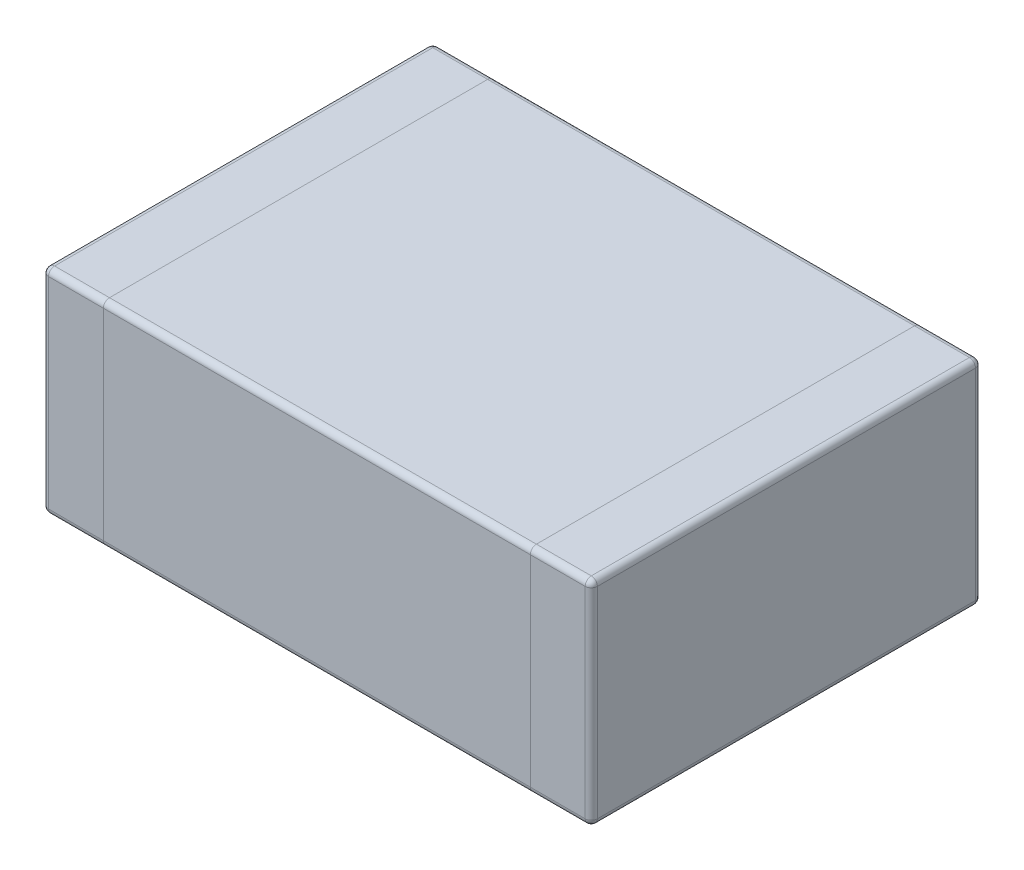
SolidWorks part; units mm, degrees
ref_plane "Front Plane" through (0, 0, 0) normal (0, 0, 1) x (1, 0, 0)
ref_plane "Top Plane" through (0, 0, 0) normal (0, 1, 0) x (1, 0, 0)
ref_plane "Right Plane" through (0, 0, 0) normal (1, 0, 0) x (0, 0, -1)
sketch "Sketch1" plane through (0, 0, 0) normal (0, 1, 0) x (1, 0, 0)
  line L1 (-2.25, -1.6) -> (2.25, -1.6)
  line L2 (-2.25, -1.6) -> (-2.25, 1.6)
  line L3 (-2.25, 1.6) -> (2.25, 1.6)
  line L4 (2.25, -1.6) -> (2.25, 1.6)
  line L5 (-2.25, -1.6) -> (2.25, 1.6) construction
  line L6 (-2.25, 1.6) -> (2.25, -1.6) construction
  point P0 (0, 0)
  dimension "D1" = 4.5
  dimension "D2" = 3.2
extrude "Extrude1" add sketch "Sketch1" along normal blind 1.75
fillet "Fillet1" radius 0.05 12 edges at (2.25, 0.875, -1.6) (-2.25, 0.875, -1.6) (-2.25, 0.875, 1.6) (2.25, 0.875, 1.6) (0, 1.75, 1.6) (-2.25, 1.75, 0) (0, 1.75, -1.6) (2.25, 1.75, 0) (0, 0, -1.6) (-2.25, 0, 0) (0, 0, 1.6) (2.25, 0, 0)
sketch "Sketch2" plane through (0, 0, 0) normal (0, 1, 0) x (1, 0, 0)
  line L0 (-2.2, 1.6) -> (2.2, 1.6) construction
  line L1 (-1.75, -1.6) -> (1.75, -1.6)
  line L2 (-1.75, -1.6) -> (-1.75, 1.6)
  line L3 (-1.75, 1.6) -> (1.75, 1.6)
  line L4 (1.75, -1.6) -> (1.75, 1.6)
  line L5 (2.2, -1.6) -> (-2.2, -1.6) construction
  line L6 (0, 1.55) -> (0, -0.6635) construction
  line L7 (2.2, 1.55) -> (-2.2, 1.55) construction
  line L9 (-2.25, -1.55) -> (-2.25, 1.55) construction
  dimension "D1" = 0.5
split line "Split Line3"
